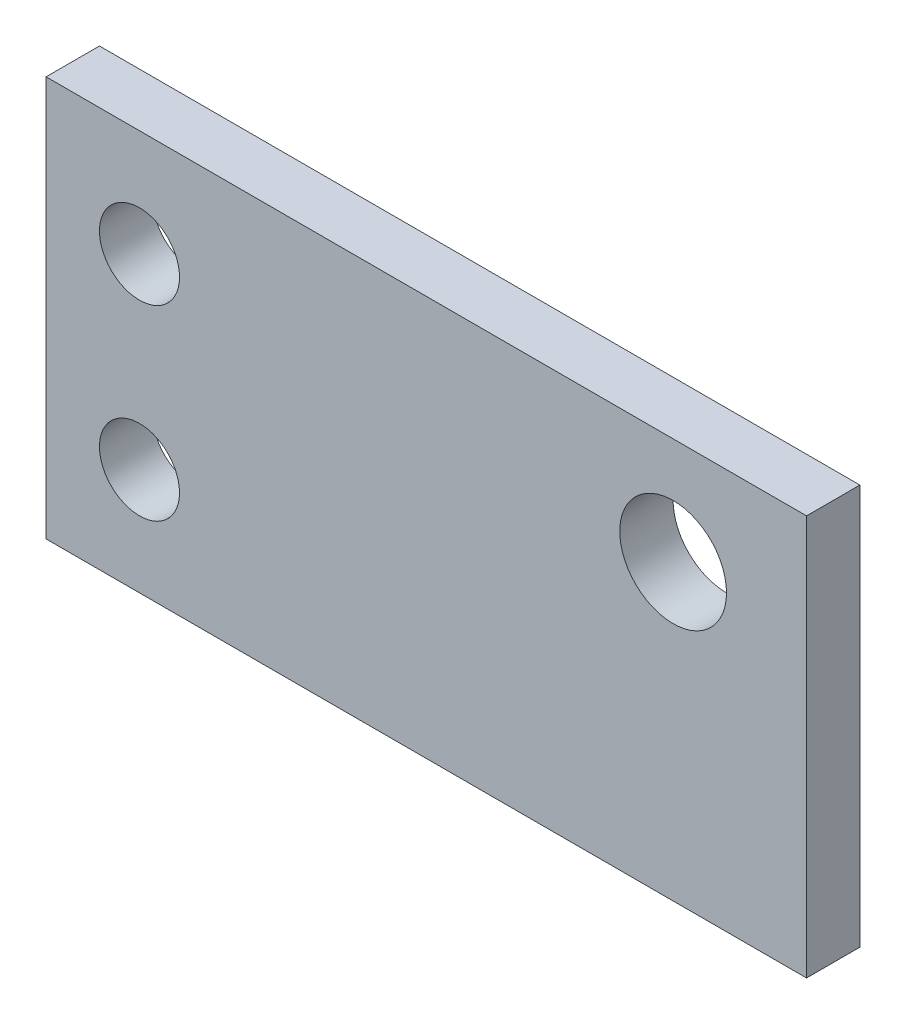
SolidWorks part; units mm, degrees
ref_plane "Plan de face" through (0, 0, 0) normal (0, 0, 1) x (1, 0, 0)
ref_plane "Plan de dessus" through (0, 0, 0) normal (0, 1, 0) x (1, 0, 0)
ref_plane "Plan de droite" through (0, 0, 0) normal (1, 0, 0) x (0, 0, -1)
sketch "Esquisse1" plane through (0, 0, 0) normal (0, 0, 1) x (1, 0, 0)
  line L1 (-25.9541, 10.0002) -> (2.5459, 10.0002)
  line L2 (-25.9541, 10.0002) -> (-25.9541, -4.9998)
  line L3 (-25.9541, -4.9998) -> (2.5459, -4.9998)
  line L4 (2.5459, 10.0002) -> (2.5459, -4.9998)
  circle A0 centre (-22.4541, -0.9998) radius 1.5
  circle A1 centre (-22.4541, 6.0002) radius 1.5
  circle A2 centre (-2.4541, 6.0002) radius 2
  dimension "D3" = 4
  dimension "D4" = 4
  dimension "D6" = 4
  dimension "D1" = 15
  dimension "D2" = 28.5
  dimension "D5" = 3.5
extrude "Extrusion1" add sketch "Esquisse1" along normal blind 2
